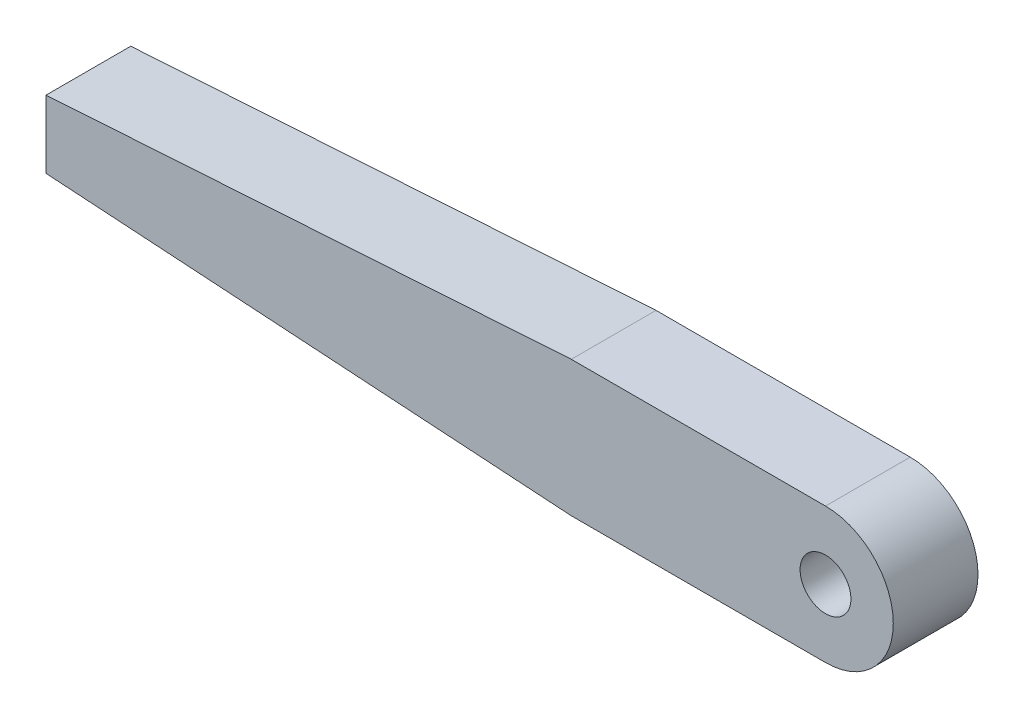
SolidWorks part; units mm, degrees
ref_plane "Plan de face" through (0, 0, 0) normal (0, 0, 1) x (1, 0, 0)
ref_plane "Plan de dessus" through (0, 0, 0) normal (0, 1, 0) x (1, 0, 0)
ref_plane "Plan de droite" through (0, 0, 0) normal (1, 0, 0) x (0, 0, -1)
sketch "Esquisse1" plane through (0, 0, 0) normal (0, 0, 1) x (1, 0, 0)
  line L0 (-31.488, 0) -> (33.1272, 0) construction
  line L4 (6, 4) -> (21, 4)
  line L5 (6, 4) -> (-25, 2)
  line L6 (-25, 2) -> (-25, -2)
  line L7 (6, -4) -> (-25, -2)
  line L8 (6, -4) -> (21, -4)
  arc A1 (21, 4) -> (21, -4) centre (21, 0) cw
  circle A2 centre (21, 0) radius 1.5
  point P13 (-25, 0)
  dimension "D1" = 46
  dimension "D2" = 4
  dimension "D6" = 3
  dimension "D3" = 15
  dimension "D4" = 2
  dimension "D5" = 25
extrude "Boss.-Extru.1" add sketch "Esquisse1" along normal blind 5
